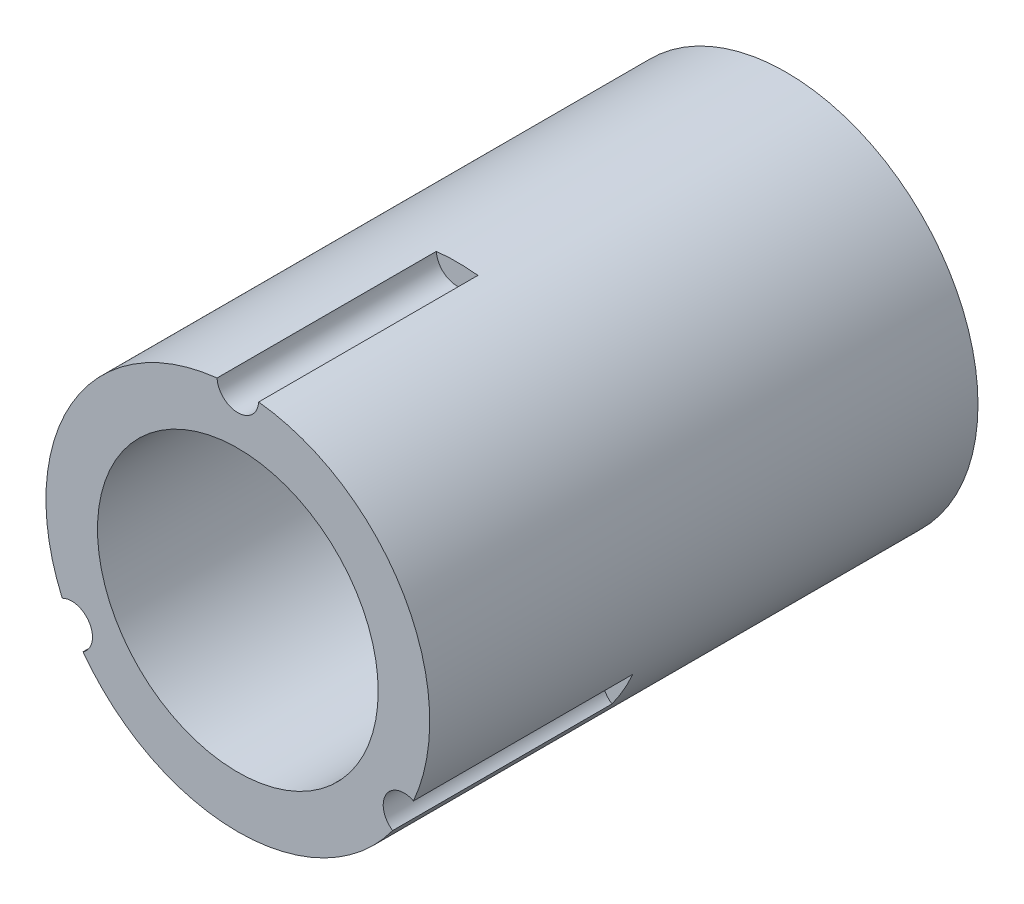
SolidWorks part; units mm, degrees
ref_plane "Plan de face" through (0, 0, 0) normal (0, 0, 1) x (1, 0, 0)
ref_plane "Plan de dessus" through (0, 0, 0) normal (0, 1, 0) x (1, 0, 0)
ref_plane "Plan de droite" through (0, 0, 0) normal (1, 0, 0) x (0, 0, -1)
sketch "Esquisse1" plane through (0, 0, 0) normal (0, 0, 1) x (1, 0, 0)
  circle A0 centre (0, 0) radius 17.5
  dimension "D1" = 35
extrude "Boss.-Extru.1" add sketch "Esquisse1" along normal blind 50 contours A0
sketch "Esquisse4" plane through (0, 0, 50) normal (0, 0, 1) x (1, 0, 0)
  circle A0 centre (0, 0) radius 12.8
extrude "Enlèv. mat.-Extru.1" cut sketch "Esquisse4" against normal blind 50
sketch "Esquisse5" plane through (0, 0, 50) normal (0, 0, 1) x (1, 0, 0)
  circle A0 centre (0, 0) radius 17.5 construction
  circle A1 centre (0, 17.5) radius 1.9
  circle A2 centre (15.1554, -8.75) radius 1.9
  circle A3 centre (-15.1554, -8.75) radius 1.9
  point P0 (0, 17.5)
  point P1 (15.1554, -8.75)
  point P4 (-15.1554, -8.75)
extrude "Enlèv. mat.-Extru.2" cut sketch "Esquisse5" against normal blind 20
